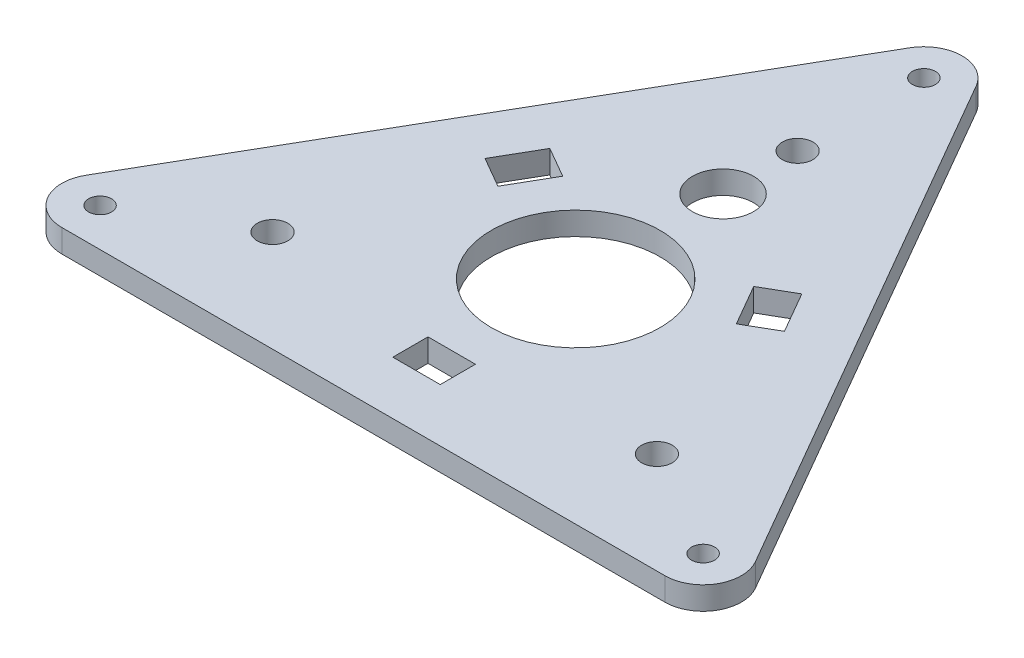
SolidWorks part; units mm, degrees
ref_plane "前视基准面" through (0, 0, 0) normal (0, 0, 1) x (1, 0, 0)
ref_plane "上视基准面" through (0, 0, 0) normal (0, 1, 0) x (1, 0, 0)
ref_plane "右视基准面" through (0, 0, 0) normal (1, 0, 0) x (0, 0, -1)
other "Configuration Table"
sketch "草图1" plane through (0, 0, 0) normal (0, 1, 0) x (1, 0, 0)
  line L0 (-4.3301, 48) -> (-43.7343, -20.25)
  line L1 (0, 45.5) -> (0, 0) construction
  line L2 (43.7343, -20.25) -> (4.3301, 48)
  line L3 (-39.4042, -27.75) -> (39.4042, -27.75)
  line L4 (0, 0) -> (0, -27.75) construction
  line L9 (-12.4796, 10.7847) -> (-16.4633, 13.0847)
  line L10 (-3.1, -16.2) -> (3.1, -16.2)
  line L11 (-3.1, -16.2) -> (-3.1, -20.8)
  line L12 (-3.1, -20.8) -> (3.1, -20.8)
  line L13 (3.1, -16.2) -> (3.1, -20.8)
  line L14 (-12.4796, 10.7847) -> (-15.5796, 5.4153)
  line L15 (-15.5796, 5.4153) -> (-19.5633, 7.7153)
  line L16 (-16.4633, 13.0847) -> (-19.5633, 7.7153)
  line L17 (15.5796, 5.4153) -> (19.5633, 7.7153)
  line L18 (15.5796, 5.4153) -> (12.4796, 10.7847)
  line L19 (12.4796, 10.7847) -> (16.4633, 13.0847)
  line L20 (19.5633, 7.7153) -> (16.4633, 13.0847)
  circle A0 centre (0, 0) radius 11.025
  circle A1 centre (0, 0) radius 45.5 construction
  circle A2 centre (0, 45.5) radius 1.5
  circle A3 centre (39.4042, -22.75) radius 1.5
  circle A4 centre (-39.4042, -22.75) radius 1.5
  arc A5 (-43.7343, -20.25) -> (-39.4042, -27.75) centre (-39.4042, -22.75) ccw
  arc A6 (4.3301, 48) -> (-4.3301, 48) centre (0, 45.5) ccw
  arc A7 (39.4042, -27.75) -> (43.7343, -20.25) centre (39.4042, -22.75) ccw
  circle A8 centre (0, 29) radius 2
  circle A9 centre (0, 0) radius 29 construction
  circle A10 centre (25.1147, -14.5) radius 2
  circle A11 centre (-25.1147, -14.5) radius 2
  circle A12 centre (0, 0) radius 19.25 construction
  circle A13 centre (0, 19.25) radius 4
  point P13 (0, 0)
  point P19 (0, 0)
  point P26 (0, 0)
  point P29 (0, 0)
  point P36 (0, -16.2)
  point P47 (0, 0)
  dimension "D1" = 91
  dimension "D2" = 3
  dimension "D6" = 5
  dimension "D7" = 58
  dimension "D8" = 4
  dimension "D10" = 22.05
  dimension "D11" = 38.5
  dimension "D12" = 8
  dimension "D13" = 6.2
  dimension "D14" = 4.6
  dimension "D15" = 6.95
  dimension "D3" = 3
  dimension "D4" = 3
  dimension "D5" = 3
  dimension "D9" = 3
  dimension "D16" = 3
extrude "凸台-拉伸1" add sketch "草图1" along normal blind 3
